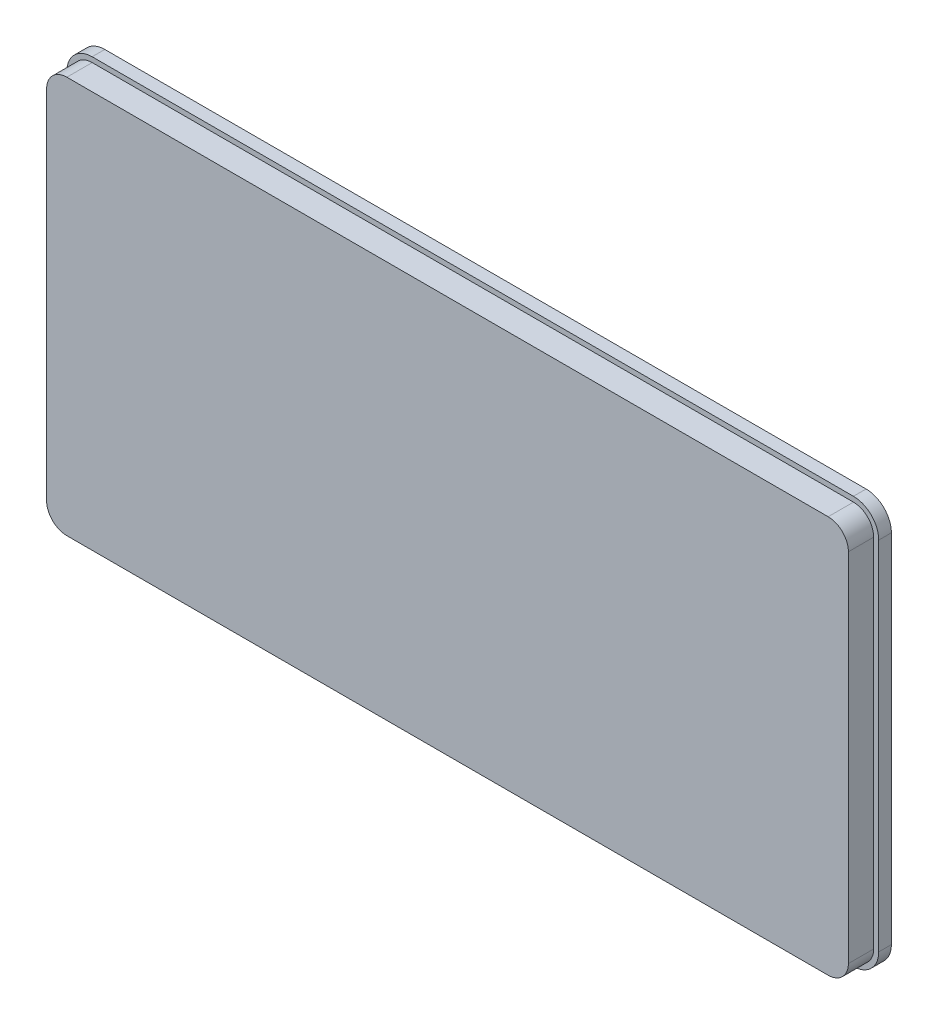
SolidWorks part; units mm, degrees
material "Стекло кварцевое прозрачное"
ref_plane "Спереди" through (0, 0, 0) normal (0, 0, 1) x (1, 0, 0)
ref_plane "Сверху" through (0, 0, 0) normal (0, 1, 0) x (1, 0, 0)
ref_plane "Справа" through (0, 0, 0) normal (1, 0, 0) x (0, 0, -1)
sketch "Sketch3" plane through (0, 0, 0) normal (0, 0, 1) x (1, 0, 0)
  line L4 (-160.5, 0) -> (160.5, 0) construction
  line L12 (0, 80.5) -> (0, -80.5) construction
  line L13 (-150.5, 80.5) -> (150.5, 80.5)
  line L14 (-160.5, 70.5) -> (-160.5, -70.5)
  line L15 (-150.5, -80.5) -> (150.5, -80.5)
  line L24 (160.5, 70.5) -> (160.5, -70.5)
  line L25 (-160.5, 80.5) -> (160.5, -80.5) construction
  line L26 (-160.5, -80.5) -> (160.5, 80.5) construction
  arc A12 (150.5, -80.5) -> (160.5, -70.5) centre (150.5, -70.5) ccw
  arc A13 (150.5, 80.5) -> (160.5, 70.5) centre (150.5, 70.5) cw
  arc A14 (-160.5, -70.5) -> (-150.5, -80.5) centre (-150.5, -70.5) ccw
  arc A15 (-150.5, 80.5) -> (-160.5, 70.5) centre (-150.5, 70.5) ccw
  point P0 (0, 0)
  dimension "D4" = 10
  dimension "D2" = 321
  dimension "D3" = 161
extrude "Boss-Extrude2" add sketch "Sketch3" against normal blind 5
sketch "Эскиз1" plane through (0, 0, 0) normal (0, 0, -1) x (-1, 0, 0)
  line L8 (-150.5, -78.5) -> (150.5, -78.5)
  line L9 (158.5, -70.5) -> (158.5, 70.5)
  line L10 (150.5, 78.5) -> (-150.5, 78.5)
  line L11 (-158.5, 70.5) -> (-158.5, -70.5)
  line L12 (-150.5, -78.5) -> (150.5, -78.5)
  line L13 (158.5, -70.5) -> (158.5, 70.5)
  line L14 (150.5, 78.5) -> (-150.5, 78.5)
  line L15 (-158.5, 70.5) -> (-158.5, -70.5)
  arc A8 (-158.5, -70.5) -> (-150.5, -78.5) centre (-150.5, -70.5) ccw
  arc A9 (150.5, -78.5) -> (158.5, -70.5) centre (150.5, -70.5) ccw
  arc A10 (158.5, 70.5) -> (150.5, 78.5) centre (150.5, 70.5) ccw
  arc A11 (-150.5, 78.5) -> (-158.5, 70.5) centre (-150.5, 70.5) ccw
  arc A12 (-158.5, -70.5) -> (-150.5, -78.5) centre (-150.5, -70.5) ccw
  arc A13 (150.5, -78.5) -> (158.5, -70.5) centre (150.5, -70.5) ccw
  arc A14 (158.5, 70.5) -> (150.5, 78.5) centre (150.5, 70.5) ccw
  arc A15 (-150.5, 78.5) -> (-158.5, 70.5) centre (-150.5, 70.5) ccw
  dimension "D1" = 2
extrude "Бобышка-Вытянуть1" add sketch "Эскиз1" against normal blind 10
equation "\"длина стекла\"=321"
equation "\"ширина стекла\"=161"
equation "\"D2@Sketch3\"=\"длина стекла\""
equation "\"D3@Sketch3\"=\"ширина стекла\""
